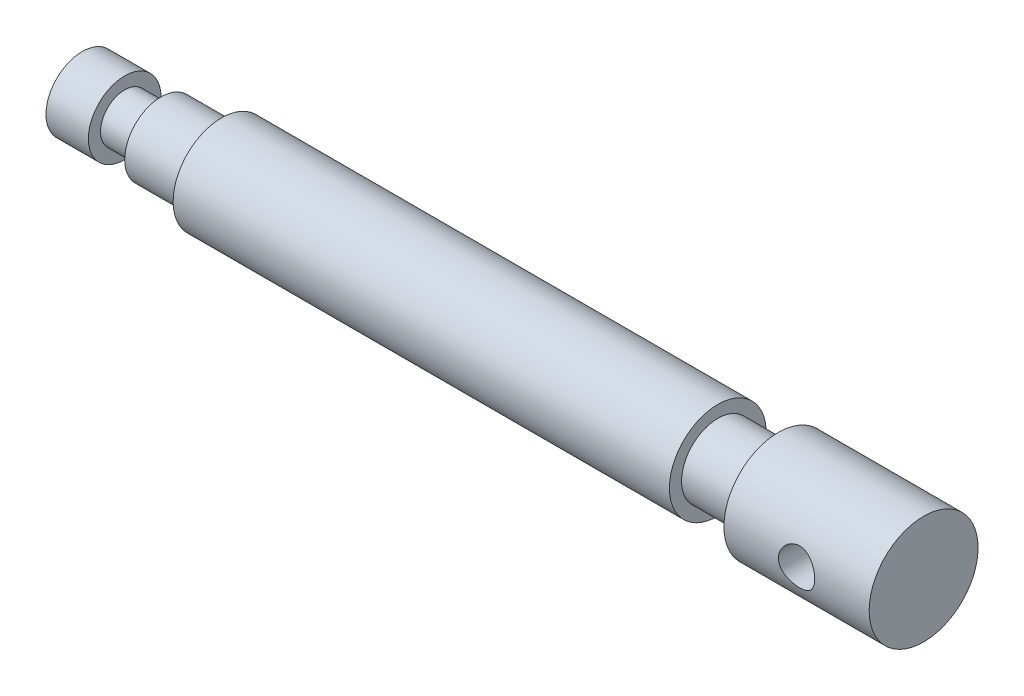
SolidWorks part; units mm, degrees
ref_plane "Front Plane" through (0, 0, 0) normal (0, 0, 1) x (1, 0, 0)
ref_plane "Top Plane" through (0, 0, 0) normal (0, 1, 0) x (1, 0, 0)
ref_plane "Right Plane" through (0, 0, 0) normal (1, 0, 0) x (0, 0, -1)
sketch "Sketch1" plane through (0, 0, 0) normal (0, 0, 1) x (1, 0, 0)
  line L0 (0, 0) -> (0, 6)
  line L1 (0, 6) -> (7, 6)
  line L2 (7, 6) -> (7, 4)
  line L3 (7, 4) -> (13, 4)
  line L4 (13, 4) -> (13, 6)
  line L5 (13, 6) -> (23, 6)
  line L6 (23, 6) -> (23, 8)
  line L7 (23, 8) -> (105, 8)
  line L8 (105, 8) -> (105, 6)
  line L9 (105, 6) -> (115, 6)
  line L10 (0, 0) -> (124.4077, 0)
  line L11 (115, 9) -> (115, 6)
  line L12 (115, 9) -> (139, 9)
  line L13 (139, 9) -> (139, 0)
  line L14 (139, 0) -> (124.4077, 0)
revolve "Revolve1" add sketch "Sketch1" angle 360 about L10
sketch "Sketch2" plane through (0, 0, 0) normal (0, 0, 1) x (1, 0, 0)
  circle A0 centre (127, 0) radius 3
extrude "Cut-Extrude3" cut sketch "Sketch2" against normal through all both and the other way through all
